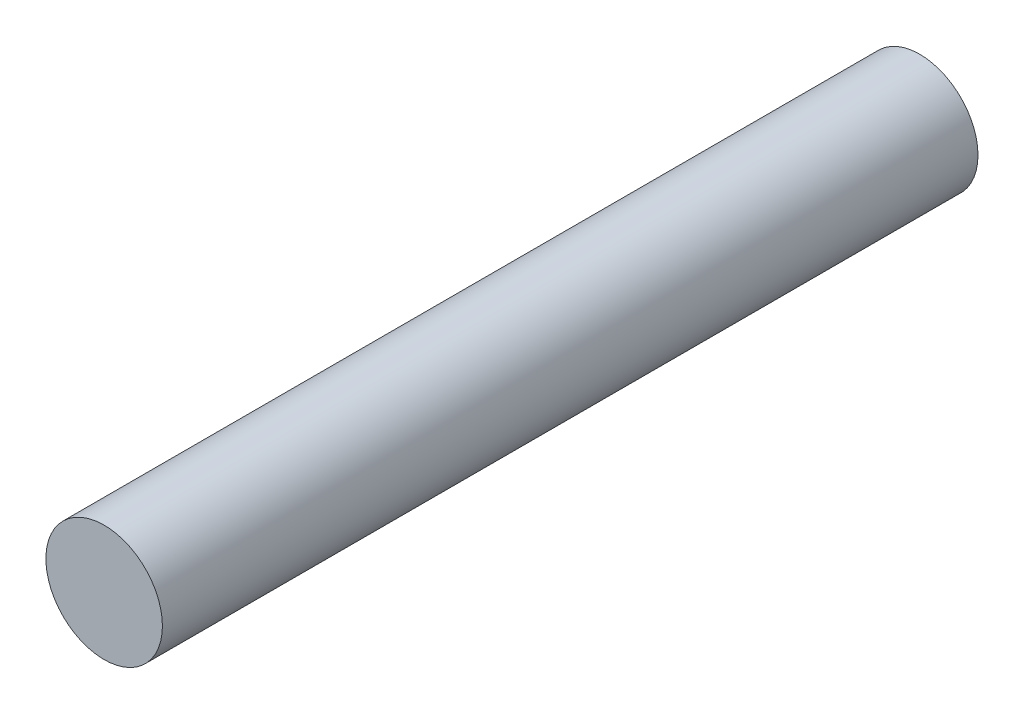
SolidWorks part; units mm, degrees
ref_plane "Front Plane" through (0, 0, 0) normal (0, 0, 1) x (1, 0, 0)
ref_plane "Top Plane" through (0, 0, 0) normal (0, 1, 0) x (1, 0, 0)
ref_plane "Right Plane" through (0, 0, 0) normal (1, 0, 0) x (0, 0, -1)
sketch "Sketch1" plane through (0, 0, 0) normal (0, 0, 1) x (1, 0, 0)
  circle A0 centre (0, 0) radius 0.25
  dimension "D1" = 0.5
extrude "Boss-Extrude1" add sketch "Sketch1" along normal blind 3.5
